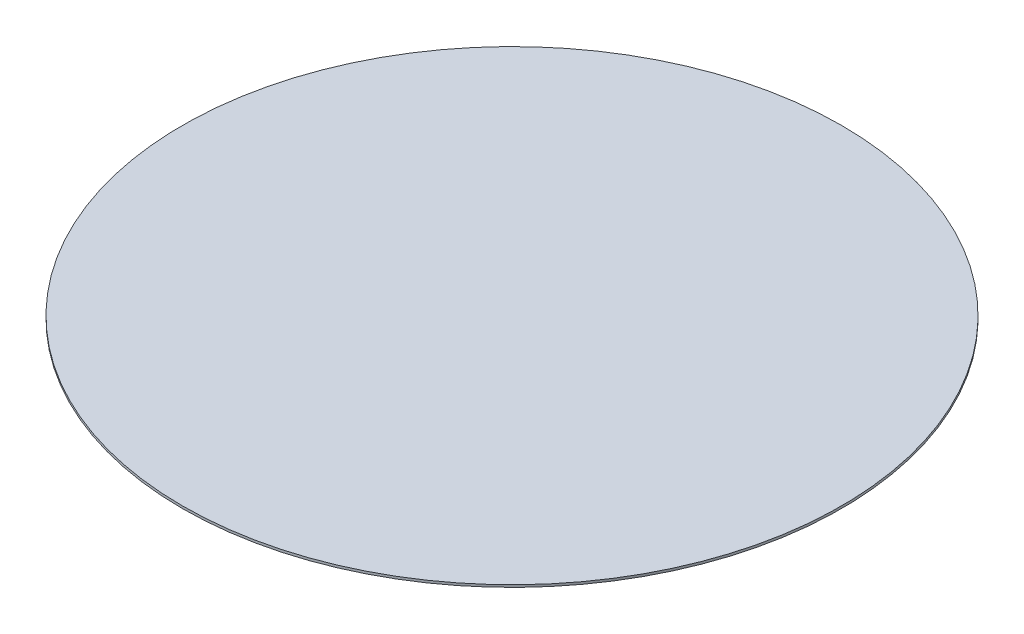
SolidWorks part; units mm, degrees
ref_plane "Front Plane" through (0, 0, 0) normal (0, 0, 1) x (1, 0, 0)
ref_plane "Top Plane" through (0, 0, 0) normal (0, 1, 0) x (1, 0, 0)
ref_plane "Right Plane" through (0, 0, 0) normal (1, 0, 0) x (0, 0, -1)
sketch "Sketch1" plane through (0, 0, 0) normal (0, 1, 0) x (1, 0, 0)
  circle A0 centre (0, 0) radius 140
  dimension "D1" = 280
extrude "Boss-Extrude1" add sketch "Sketch1" along normal blind 1
